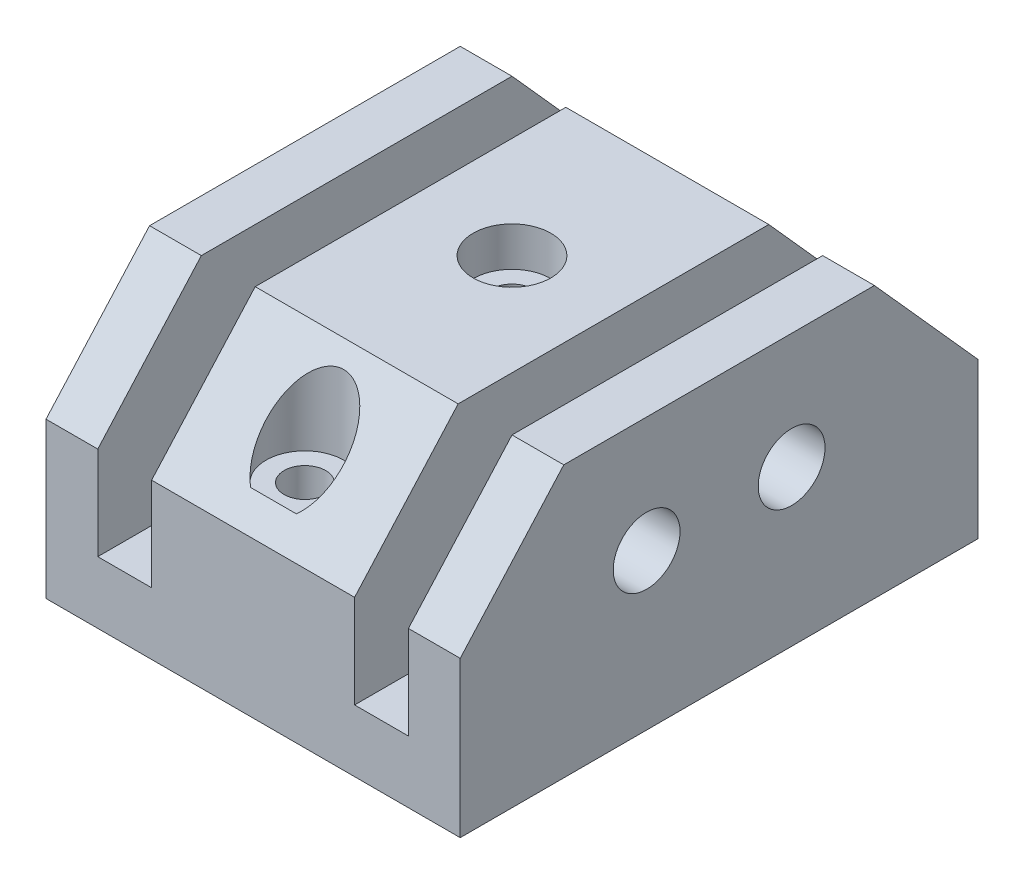
SolidWorks part; units mm, degrees
ref_plane "Front Plane" through (0, 0, 0) normal (0, 0, 1) x (1, 0, 0)
ref_plane "Top Plane" through (0, 0, 0) normal (0, 1, 0) x (1, 0, 0)
ref_plane "Right Plane" through (0, 0, 0) normal (1, 0, 0) x (0, 0, -1)
sketch "Sketch1" plane through (0, 0, 0) normal (1, 0, 0) x (0, 0, -1)
  line L1 (0, 0) -> (63.5, 0)
  line L2 (0, 0) -> (0, 6.35)
  line L3 (0, 6.35) -> (63.5, 6.35)
  line L4 (63.5, 0) -> (63.5, 6.35)
  dimension "D1" = 6.35
  dimension "D2" = 63.5
extrude "Boss-Extrude1" add sketch "Sketch1" against normal blind 50.8
sketch "Sketch2" plane through (0, 0, 0) normal (1, 0, 0) x (0, 0, -1)
  line L0 (0, 6.35) -> (0, 19.05)
  line L1 (0, 19.05) -> (12.7, 33.249)
  line L2 (12.7, 33.249) -> (50.8, 33.249)
  line L3 (50.8, 33.249) -> (63.5, 19.05)
  line L4 (63.5, 19.05) -> (63.5, 6.35)
  line L5 (63.5, 6.35) -> (0, 6.35)
  point P7 (31.75, 33.249)
  point P10 (31.75, 6.35)
  dimension "D1" = 38.1
  dimension "D2" = 12.7
  dimension "D3" = 12.7
  dimension "D4" = 19.05
  dimension "D5" = 19.05
extrude "Boss-Extrude2" add sketch "Sketch2" against normal blind 50.8
sketch "Sketch10" plane through (0, 0, -63.5) normal (0, 0, -1) x (-1, 0, 0)
  line L1 (50.8, 33.249) -> (0, 33.249) construction
  line L3 (6.35, 7.62) -> (6.35, 33.249)
  line L4 (6.35, 33.249) -> (12.954, 33.249)
  line L5 (12.954, 7.62) -> (12.954, 33.249)
  line L6 (6.35, 7.62) -> (12.954, 7.62)
  line L8 (50.8, 0) -> (0, 0) construction
  point P11 (12.954, 7.62)
  dimension "D1" = 7.62
  dimension "D2" = 6.604
  dimension "D3" = 6.35
extrude "Cut-Extrude1" cut sketch "Sketch10" against normal through all
pattern_linear "LPattern3" count 2 spacing 31.496 along (-1, 0, 0) of "Cut-Extrude1"
sketch "Sketch11" plane through (0, 0, 0) normal (1, 0, 0) x (0, 0, -1)
  circle A0 centre (22.86, 19.05) radius 4.0957
  circle A1 centre (22.86, 19.05) radius 7.9375 construction
  circle A2 centre (40.64, 19.05) radius 4.0958
  circle A3 centre (40.64, 19.05) radius 7.9375 construction
  dimension "D1" = 8.1915
  dimension "D3" = 15.875
  dimension "D4" = 8.1915
  dimension "D6" = 15.875
  dimension "D2" = 10.16
  dimension "D5" = 10.16
extrude "Cut-Extrude2" cut sketch "Sketch11" against normal through all
sketch "Sketch14" plane through (0, 33.249, 0) normal (0, 1, 0) x (1, 0, 0)
  line L3 (-37.846, 12.7) -> (-37.846, 50.8) construction
  point P0 (-25.4, 31.75)
  point P4 (-37.846, 31.75)
  dimension "D1" = 12.446
hole_wizard "CBORE for #10 Socket Head Cap Screw1" positions "Sketch15" profile "Sketch16" counterbore size "#10" standard "ANSI Inch" end condition up to next
sketch "Sketch15" plane through (0, 33.249, 0) normal (0, 1, 0) x (1, 0, 0)
  point P0 (-25.4, 31.75)
sketch "Sketch16" plane through (-25.4, 33.249, -31.75) normal (1, 0, 0) x (0, 0, 1)
  line L0 (0, 0) -> (0, 33.249)
  line L1 (0, 33.249) -> (2.5527, 33.249)
  line L3 (2.5527, 33.249) -> (2.5527, 4.826)
  line L4 (2.5527, 4.826) -> (4.7625, 4.826)
  line L5 (4.7625, 4.826) -> (4.7625, 0)
  line L7 (4.7625, 0) -> (0, 0)
  line L11 (0, -6.35) -> (0, 107.95) construction
  dimension "Thru Hole Dia." = 5.1054
  dimension "Thru Hole Depth" = 33.249
  dimension "C'Bore Dia." = 9.525
  dimension "C'Bore Depth" = 4.826
sketch "Sketch17" plane through (0, 40.0201, -44.7438) normal (0, 0.6667, -0.7454) x (-1, 0, 0)
  line L0 (12.954, -28.1343) -> (12.954, -9.0843) construction
  line L1 (37.846, -9.0843) -> (12.954, -9.0843) construction
  point P0 (25.4, -18.6093)
  point P4 (12.954, -18.6093)
  point P7 (25.4, -9.0843)
sketch "Sketch18" plane through (0, 8.4667, 9.466) normal (0, 0.6667, 0.7454) x (1, 0, 0)
  line L0 (-12.954, 33.249) -> (-12.954, 14.199) construction
  line L1 (-37.846, 33.249) -> (-12.954, 33.249) construction
  point P0 (-25.4, 23.724)
  point P1 (-25.4, 23.724)
  point P4 (-12.954, 23.724)
  point P7 (-25.4, 33.249)
ref_plane "Plane2" through (0, 33.02, 0) normal (0, -1, 0) x (-1, 0, 0)
hole_wizard "CBORE for #10 Socket Head Cap Screw3" positions "Sketch24" profile "Sketch25" counterbore size "#10" standard "ANSI Inch" end condition up to next
sketch "Sketch24" plane through (0, 33.02, 0) normal (0, -1, 0) x (-1, 0, 0)
  point P0 (25.4, 6.35)
  point P2 (25.4, 57.15)
sketch "Sketch25" plane through (-25.4, 33.02, -6.35) normal (1, 0, 0) x (0, 0, 1)
  line L0 (0, 0) -> (0, 33.02)
  line L1 (0, 33.02) -> (2.5527, 33.02)
  line L3 (2.5527, 33.02) -> (2.5527, 11.176)
  line L4 (2.5527, 11.176) -> (4.7625, 11.176)
  line L5 (4.7625, 11.176) -> (4.7625, 0)
  line L7 (4.7625, 0) -> (0, 0)
  line L11 (0, -6.35) -> (0, 107.95) construction
  dimension "Thru Hole Dia." = 5.1054
  dimension "Thru Hole Depth" = 33.02
  dimension "C'Bore Dia." = 9.525
  dimension "C'Bore Depth" = 11.176
ref_plane "midplane" through (0, 0, -31.75) normal (0, 0, -1) x (-1, 0, 0)
